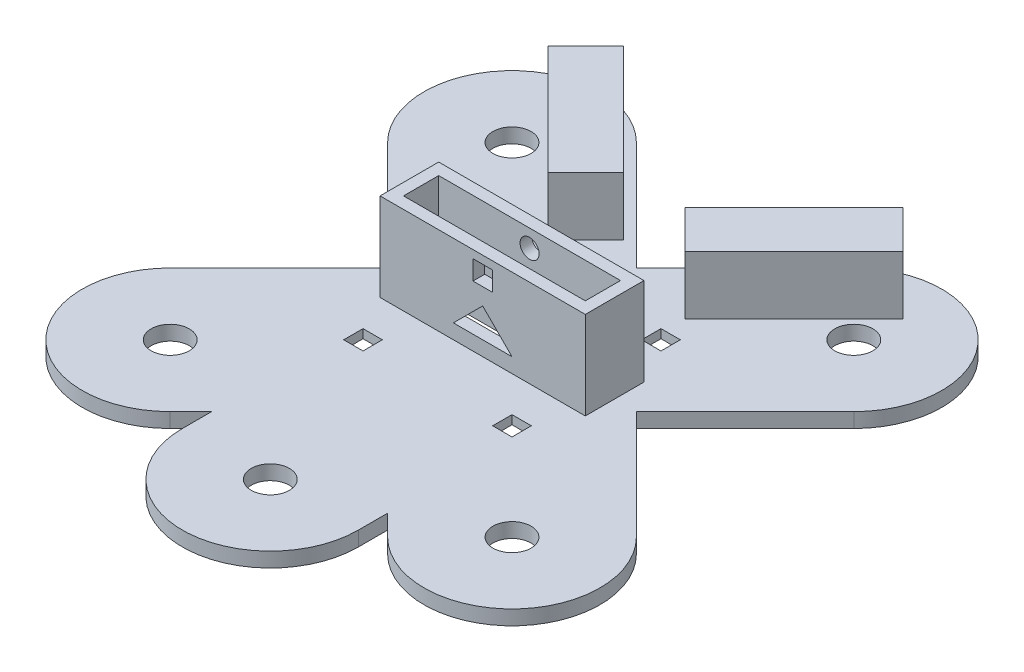
SolidWorks part; units mm, degrees
ref_plane "Front" through (0, 0, 0) normal (0, 0, 1) x (1, 0, 0)
ref_plane "Top" through (0, 0, 0) normal (0, 1, 0) x (1, 0, 0)
ref_plane "Right" through (0, 0, 0) normal (1, 0, 0) x (0, 0, -1)
sketch "Esquisse2" plane through (0, 0, 0) normal (0, 1, 0) x (1, 0, 0)
  line L0 (-30, 30) -> (30, -30) construction
  line L1 (30, 30) -> (30, -30) construction
  line L2 (30, -30) -> (-30, -30) construction
  line L3 (-30, -30) -> (-30, 30) construction
  line L4 (-30, 30) -> (30, 30) construction
  line L5 (30, 30) -> (-30, -30) construction
  line L6 (-1.7157, 1.7157) -> (-58.2843, 58.2843) construction
  line L7 (-22.9289, -19.4975) -> (-79.4975, 37.0711)
  line L8 (19.4975, 22.9289) -> (-37.0711, 79.4975)
  line L11 (5, 11.5685) -> (5, 91.5685) construction
  line L15 (1.7157, 1.7157) -> (58.2843, 58.2843) construction
  line L16 (-19.4975, 22.9289) -> (37.0711, 79.4975)
  line L17 (21.5685, -5) -> (101.5685, -5) construction
  line L20 (22.9289, -19.4975) -> (79.4975, 37.0711)
  line L28 (1.7157, -1.7157) -> (58.2843, -58.2843) construction
  line L29 (-11.5685, -5) -> (-91.5685, -5) construction
  line L30 (22.9289, 19.4975) -> (79.4975, -37.0711)
  line L31 (-19.4975, -22.9289) -> (37.0711, -79.4975)
  line L32 (0, -2.4264) -> (0, -82.4264) construction
  line L33 (30, -2.4264) -> (30, -82.4264)
  line L34 (-30, -2.4264) -> (-30, -82.4264)
  line L35 (-1.7157, -1.7157) -> (-58.2843, -58.2843) construction
  line L36 (19.4975, -22.9289) -> (-37.0711, -79.4975)
  line L37 (-22.9289, 19.4975) -> (-79.4975, -37.0711)
  line L59 (0, 2.4264) -> (0, 82.4264) construction
  line L60 (-30, 2.4264) -> (-30, 82.4264)
  line L61 (30, 2.4264) -> (30, 82.4264)
  line L62 (2.4264, 0) -> (82.4264, 0) construction
  line L63 (2.4264, 30) -> (82.4264, 30)
  line L64 (2.4264, -30) -> (82.4264, -30)
  line L65 (-2.4264, 0) -> (-82.4264, 0) construction
  line L66 (-2.4264, -30) -> (-82.4264, -30)
  line L67 (-2.4264, 30) -> (-82.4264, 30)
  line L68 (0, 2.4264) -> (0, 82.4264) construction
  line L69 (-30, 2.4264) -> (-30, 82.4264)
  line L70 (30, 2.4264) -> (30, 82.4264)
  line L71 (2.4264, 0) -> (82.4264, 0) construction
  line L72 (2.4264, 30) -> (82.4264, 30)
  line L73 (2.4264, -30) -> (82.4264, -30)
  line L74 (-2.4264, 0) -> (-82.4264, 0) construction
  line L75 (-2.4264, -30) -> (-82.4264, -30)
  line L76 (-2.4264, 30) -> (-82.4264, 30)
  arc A0 (-22.9289, -19.4975) -> (19.4975, 22.9289) centre (-1.7157, 1.7157) ccw
  arc A1 (-37.0711, 79.4975) -> (-79.4975, 37.0711) centre (-58.2843, 58.2843) ccw
  arc A6 (-19.4975, 22.9289) -> (22.9289, -19.4975) centre (1.7157, 1.7157) ccw
  arc A7 (79.4975, 37.0711) -> (37.0711, 79.4975) centre (58.2843, 58.2843) ccw
  arc A16 (22.9289, 19.4975) -> (-19.4975, -22.9289) centre (1.7157, -1.7157) ccw
  arc A17 (37.0711, -79.4975) -> (79.4975, -37.0711) centre (58.2843, -58.2843) ccw
  arc A18 (30, -2.4264) -> (-30, -2.4264) centre (0, -2.4264) ccw
  arc A19 (-30, -82.4264) -> (30, -82.4264) centre (0, -82.4264) ccw
  arc A20 (19.4975, -22.9289) -> (-22.9289, 19.4975) centre (-1.7157, -1.7157) ccw
  arc A21 (-79.4975, -37.0711) -> (-37.0711, -79.4975) centre (-58.2843, -58.2843) ccw
  arc A42 (-30, 2.4264) -> (30, 2.4264) centre (0, 2.4264) ccw
  arc A43 (30, 82.4264) -> (-30, 82.4264) centre (0, 82.4264) ccw
  arc A44 (2.4264, 30) -> (2.4264, -30) centre (2.4264, 0) ccw
  arc A45 (82.4264, -30) -> (82.4264, 30) centre (82.4264, 0) ccw
  arc A46 (-2.4264, -30) -> (-2.4264, 30) centre (-2.4264, 0) ccw
  arc A47 (-82.4264, 30) -> (-82.4264, -30) centre (-82.4264, 0) ccw
  point P0 (0, 0)
  point P9 (-30, 30)
  point P19 (5, 51.5685)
  point P22 (0, 49.4975)
  point P29 (30, 30)
  point P33 (61.5685, -5)
  point P39 (49.4975, 0)
  point P46 (30, -30)
  point P53 (0, -42.4264)
  point P61 (-51.5685, -5)
  point P63 (-30, -30)
  point P66 (5, -5)
  point P71 (-49.4975, 0)
  point P76 (0, 0)
  point P109 (0, 49.4975)
  point P116 (49.4975, 0)
  point P123 (-49.4975, 0)
  point P130 (0, 42.4264)
  point P137 (42.4264, 0)
  point P144 (-42.4264, 0)
  point P151 (0, 42.4264)
  point P158 (42.4264, 0)
  point P165 (-42.4264, 0)
  point P172 (0, 42.4264)
  point P179 (42.4264, 0)
  point P186 (-42.4264, 0)
  dimension "D4" = 30
  dimension "D1" = 60
  dimension "D2" = 60
  dimension "D3" = 80
  dimension "D5" = 8
extrude "Boss.-Extru.1" add sketch "Esquisse2" along normal blind 5
sketch "Esquisse4" plane through (0, 0, 0) normal (0, -1, 0) x (-1, 0, 0)
  line L0 (0, 0) -> (-79.4975, -79.4975) construction
  line L1 (-25.317, -46.5302) -> (-7.6393, -28.8525)
  line L2 (-7.6393, -28.8525) -> (-28.8525, -7.6393)
  line L3 (-28.8525, -7.6393) -> (-46.5302, -25.317)
  line L4 (-42.4264, 0) -> (-79.4975, -37.0711) construction
  line L5 (-46.5302, 25.317) -> (-28.8525, 7.6393)
  line L6 (-7.6393, 28.8525) -> (-25.317, 46.5302)
  line L7 (-28.8525, 7.6393) -> (-7.6393, 28.8525)
  line L8 (25.317, 46.5302) -> (7.6393, 28.8525)
  line L9 (28.8525, 7.6393) -> (46.5302, 25.317)
  line L10 (7.6393, 28.8525) -> (28.8525, 7.6393)
  line L11 (46.5302, -25.317) -> (28.8525, -7.6393)
  line L12 (7.6393, -28.8525) -> (25.317, -46.5302)
  line L13 (28.8525, -7.6393) -> (7.6393, -28.8525)
  arc A0 (-79.4975, -37.0711) -> (-37.0711, -79.4975) centre (-58.2843, -58.2843) ccw construction
  arc A1 (-25.317, -46.5302) -> (-46.5302, -25.317) centre (-58.2843, -58.2843) ccw
  arc A2 (-46.5302, 25.317) -> (-25.317, 46.5302) centre (-58.2843, 58.2843) ccw
  arc A3 (25.317, 46.5302) -> (46.5302, 25.317) centre (58.2843, 58.2843) ccw
  arc A4 (46.5302, -25.317) -> (25.317, -46.5302) centre (58.2843, -58.2843) ccw
  point P36 (0, 0)
  dimension "D5" = 35
  dimension "D1" = 25
  dimension "D2" = 25
  dimension "D3" = 15
  dimension "D4" = 30
extrude "Enlèv. mat.-Extru.1" cut sketch "Esquisse4" against normal blind 2 contours L0 L2 L3 A1 | L2 L0 A1 L1 | A2 L5 L7 L6 | A3 L8 L10 L9 | A4 L11 L13 L12
sketch "Esquisse7" plane through (0, 0, 0) normal (0, -1, 0) x (-1, 0, 0)
  circle A0 centre (0, -82.4264) radius 6.5
  circle A1 centre (-58.2843, -58.2843) radius 6.5
  circle A2 centre (-82.4264, 0) radius 6.5 [skipped]
  circle A3 centre (-58.2843, 58.2843) radius 6.5
  circle A4 centre (0, 82.4264) radius 6.5 [skipped]
  circle A5 centre (58.2843, 58.2843) radius 6.5
  circle A6 centre (82.4264, 0) radius 6.5 [skipped]
  circle A7 centre (58.2843, -58.2843) radius 6.5
  point P20 (0, 0)
  dimension "D1" = 13
extrude "Enlèv. mat.-Extru.3" cut sketch "Esquisse7" against normal through all
sketch "Esquisse10" plane through (0, 5, 0) normal (0, 1, 0) x (1, 0, 0)
  line L0 (58.2843, -58.2843) -> (0, 0) construction
  circle A0 centre (25.4038, -25.4038) radius 3.175
  circle A1 centre (-25.4038, -25.4038) radius 3.175
  circle A2 centre (-25.4038, 25.4038) radius 3.175
  circle A3 centre (25.4038, 25.4038) radius 3.175
  point P15 (0, 0)
  dimension "D1" = 6.35
  dimension "D2" = 46.5
extrude "Enlèv. mat.-Extru.4" cut sketch "Esquisse10" against normal through all
sketch "Esquisse11" plane through (0, 5, 0) normal (0, 1, 0) x (1, 0, 0)
  line L0 (-22.1038, -28.7038) -> (-28.7038, -28.7038)
  line L1 (28.7038, -22.1038) -> (22.1038, -22.1038)
  line L2 (28.7038, -22.1038) -> (28.7038, -28.7038)
  line L3 (28.7038, -28.7038) -> (22.1038, -28.7038)
  line L4 (22.1038, -22.1038) -> (22.1038, -28.7038)
  line L5 (28.7038, -22.1038) -> (22.1038, -28.7038) construction
  line L6 (28.7038, -28.7038) -> (22.1038, -22.1038) construction
  line L7 (-22.1038, -28.7038) -> (-22.1038, -22.1038)
  line L8 (-22.1038, -22.1038) -> (-28.7038, -22.1038)
  line L9 (-28.7038, -28.7038) -> (-28.7038, -22.1038)
  line L10 (-28.7038, 22.1038) -> (-28.7038, 28.7038)
  line L11 (-28.7038, 22.1038) -> (-22.1038, 22.1038)
  line L12 (-22.1038, 22.1038) -> (-22.1038, 28.7038)
  line L13 (-28.7038, 28.7038) -> (-22.1038, 28.7038)
  line L14 (22.1038, 28.7038) -> (28.7038, 28.7038)
  line L15 (22.1038, 28.7038) -> (22.1038, 22.1038)
  line L16 (22.1038, 22.1038) -> (28.7038, 22.1038)
  line L17 (28.7038, 28.7038) -> (28.7038, 22.1038)
  point P0 (25.4038, -25.4038)
  point P21 (0, 0)
  dimension "D1" = 6.6
  dimension "D2" = 6.6
extrude "Enlèv. mat.-Extru.5" cut sketch "Esquisse11" against normal blind 3.5
sketch "Esquisse16" plane through (0, 5, 0) normal (0, 1, 0) x (1, 0, 0)
  line L0 (47.7021, 85.6982) -> (10.478, 48.4742)
  line L1 (10.478, 48.4742) -> (23.3404, 35.6118)
  line L2 (23.3404, 35.6118) -> (60.5645, 72.8359)
  line L3 (60.5645, 72.8359) -> (47.7021, 85.6982)
  line L4 (0, -50) -> (0, 50) construction
  line L5 (-23.3404, 35.6118) -> (-60.5645, 72.8359)
  line L6 (-10.478, 48.4742) -> (-23.3404, 35.6118)
  line L7 (-47.7021, 85.6982) -> (-10.478, 48.4742)
  line L8 (-60.5645, 72.8359) -> (-47.7021, 85.6982)
extrude "Boss.-Extru.8" add sketch "Esquisse16" along normal blind 20
sketch "Esquisse18" plane through (0, 5, 0) normal (0, 1, 0) x (1, 0, 0)
  line L1 (-35, 10) -> (35, 10)
  line L2 (-35, 10) -> (-35, -10)
  line L3 (-35, -10) -> (35, -10)
  line L4 (35, 10) -> (35, -10)
  line L5 (-35, 10) -> (35, -10) construction
  line L6 (-35, -10) -> (35, 10) construction
  line L7 (-31, 6) -> (31, 6)
  line L8 (-31, 6) -> (-31, -6)
  line L9 (-31, -6) -> (31, -6)
  line L10 (31, 6) -> (31, -6)
  line L11 (-31, 6) -> (31, -6) construction
  line L12 (-31, -6) -> (31, 6) construction
  point P0 (0, 0)
  point P6 (0, 0)
  dimension "D1" = 20
  dimension "D2" = 70
  dimension "D3" = 62
  dimension "D4" = 12
extrude "Boss.-Extru.9" add sketch "Esquisse18" along normal blind 30
sketch "Esquisse19" plane through (0, 0, 10) normal (0, 0, 1) x (1, 0, 0)
  line L0 (-35, 35) -> (35, 35) construction
  line L1 (35, 35) -> (35, 5) construction
  circle A0 centre (0, 29) radius 3.25
  dimension "D1" = 6.5
  dimension "D2" = 6
  dimension "D3" = 35
extrude "Enlèv. mat.-Extru.6" cut sketch "Esquisse19" against normal through all
sketch "Esquisse20" plane through (0, 0, 10) normal (0, 0, 1) x (1, 0, 0)
  line L1 (-3.3, 32.3) -> (3.3, 32.3)
  line L2 (-3.3, 32.3) -> (-3.3, 25.7)
  line L3 (-3.3, 25.7) -> (3.3, 25.7)
  line L4 (3.3, 32.3) -> (3.3, 25.7)
  line L5 (-3.3, 32.3) -> (3.3, 25.7) construction
  line L6 (-3.3, 25.7) -> (3.3, 32.3) construction
  point P0 (0, 29)
  dimension "D1" = 6.6
  dimension "D2" = 6.6
extrude "Enlèv. mat.-Extru.7" cut sketch "Esquisse20" against normal blind 4
sketch "Esquisse21" plane through (0, 5, 0) normal (0, 1, 0) x (1, 0, 0)
  line L1 (-20, -5) -> (20, -5)
  line L2 (-20, -5) -> (-20, 5)
  line L3 (-20, 5) -> (20, 5)
  line L4 (20, -5) -> (20, 5)
  line L5 (-20, -5) -> (20, 5) construction
  line L6 (-20, 5) -> (20, -5) construction
  point P0 (0, 0)
  dimension "D1" = 10
  dimension "D2" = 40
extrude "Enlèv. mat.-Extru.8" cut sketch "Esquisse21" against normal through all
sketch "Esquisse22" plane through (0, 0, -10) normal (0, 0, -1) x (-1, 0, 0)
  line L0 (-10, 10) -> (10, 10)
  line L1 (10, 10) -> (0, 20)
  line L2 (0, 20) -> (-10, 10)
  line L3 (35, 35) -> (35, 5) construction
  line L4 (-35, 5) -> (35, 5) construction
  dimension "D1" = 45
  dimension "D2" = 45
  dimension "D3" = 20
  dimension "D4" = 35
  dimension "D5" = 5
extrude "Enlèv. mat.-Extru.9" cut sketch "Esquisse22" against normal through all
